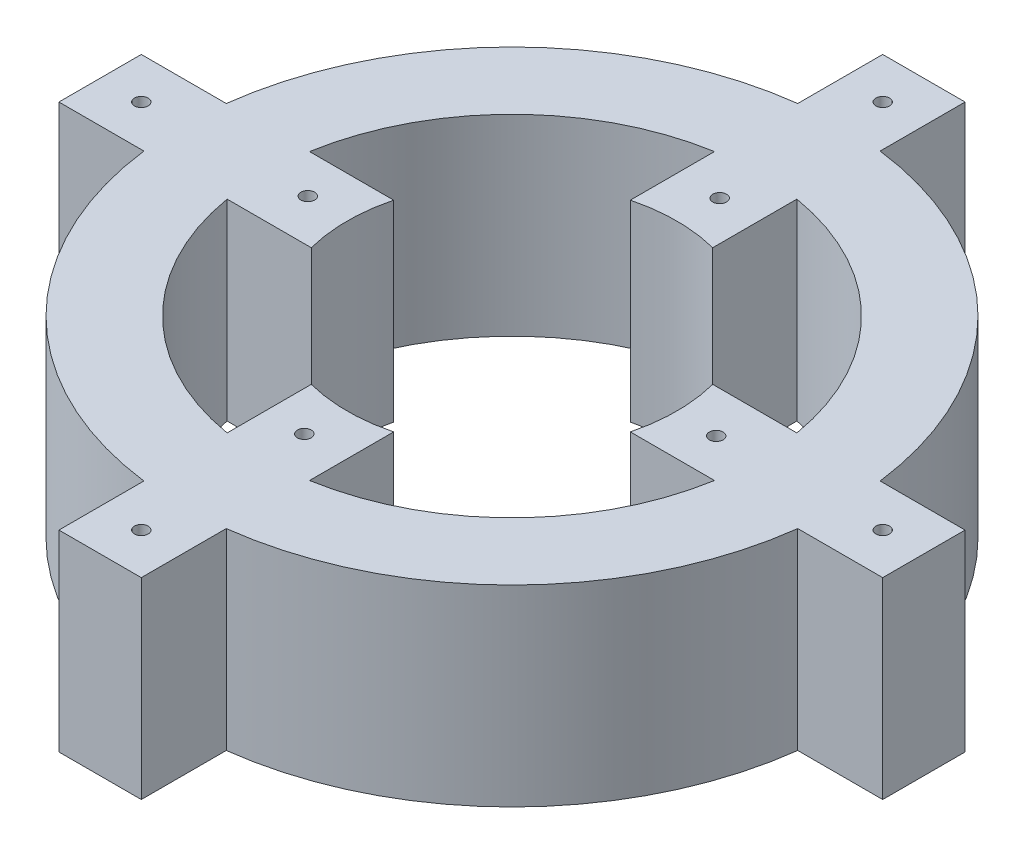
SolidWorks part; units mm, degrees
ref_plane "Спереди" through (0, 0, 0) normal (0, 0, 1) x (1, 0, 0)
ref_plane "Сверху" through (0, 0, 0) normal (0, 1, 0) x (1, 0, 0)
ref_plane "Справа" through (0, 0, 0) normal (1, 0, 0) x (0, 0, -1)
sketch "Эскиз1" plane through (0, 0, 0) normal (0, 1, 0) x (1, 0, 0)
  line L0 (-4.0901, 152.4) -> (-4.0901, -153.2035) construction
  line L1 (-4.0901, -153.2035) -> (-156.4901, -0.8035) construction
  line L2 (-156.4901, -0.8035) -> (148.3099, -0.8035) construction
  line L3 (-111.8532, 106.9595) -> (103.6729, -108.5666) construction
  line L4 (-111.8532, -108.5666) -> (103.6729, 106.9595) construction
  line L5 (-156.4901, 151.5965) -> (-156.4901, -153.2035) construction
  line L6 (-156.4901, -153.2035) -> (148.3099, -153.2035) construction
  line L7 (148.3099, -153.2035) -> (148.3099, 151.5965) construction
  line L8 (148.3099, 151.5965) -> (-156.4901, 151.5965) construction
  line L9 (-118.3901, 113.4965) -> (-118.3901, -115.1035) construction
  line L10 (-118.3901, -115.1035) -> (110.2099, -115.1035) construction
  line L11 (110.2099, -115.1035) -> (110.2099, 113.4965) construction
  line L12 (110.2099, 113.4965) -> (-118.3901, 113.4965) construction
  line L13 (-80.2901, 113.4965) -> (-80.2901, -115.1035) construction
  line L14 (-77.8705, 18.2465) -> (-116.7915, 18.2465)
  line L15 (-194.5901, -0.8035) -> (-80.2901, -0.8035) construction
  line L16 (-77.8705, -19.8535) -> (-116.7915, -19.8535)
  line L17 (-194.5901, 18.2465) -> (-194.5901, -19.8535)
  line L18 (-155.2948, 18.2465) -> (-194.5901, 18.2465)
  line L19 (-155.2948, -19.8535) -> (-194.5901, -19.8535)
  line L20 (14.9599, 189.6965) -> (-23.1401, 189.6965)
  line L21 (14.9599, 150.4012) -> (14.9599, 189.6965)
  line L22 (-23.1401, 150.4012) -> (-23.1401, 189.6965)
  line L23 (14.9599, 72.9768) -> (14.9599, 111.8978)
  line L24 (-23.1401, 72.9768) -> (-23.1401, 111.8978)
  line L27 (-4.0901, 151.5965) -> (-4.0901, -153.2035) construction
  line L28 (-4.0901, 189.6965) -> (-4.0901, 75.3965) construction
  line L29 (186.4099, -19.8535) -> (186.4099, 18.2465)
  line L30 (147.1145, -19.8535) -> (186.4099, -19.8535)
  line L31 (147.1145, 18.2465) -> (186.4099, 18.2465)
  line L32 (69.6902, -19.8535) -> (108.6112, -19.8535)
  line L33 (69.6902, 18.2465) -> (108.6112, 18.2465)
  line L34 (148.3099, -0.8035) -> (-156.4901, -0.8035) construction
  line L35 (186.4099, -0.8035) -> (72.1099, -0.8035) construction
  line L36 (-23.1401, -191.3035) -> (14.9599, -191.3035)
  line L37 (-23.1401, -152.0082) -> (-23.1401, -191.3035)
  line L38 (14.9599, -152.0082) -> (14.9599, -191.3035)
  line L39 (-23.1401, -74.5839) -> (-23.1401, -113.5049)
  line L40 (14.9599, -74.5839) -> (14.9599, -113.5049)
  line L41 (-4.0901, -153.2035) -> (-4.0901, 151.5965) construction
  line L42 (-4.0901, -191.3035) -> (-4.0901, -77.0035) construction
  arc A0 (-155.2948, -19.8535) -> (-111.8532, -108.5666) centre (-4.0901, -0.8035) ccw
  arc A1 (-116.7915, -19.8535) -> (-23.1401, -113.5049) centre (-4.0901, -0.8035) ccw
  arc A2 (-77.8705, 18.2465) -> (-77.8705, -19.8535) centre (-4.0901, -0.8035) ccw
  circle A3 centre (-175.5401, -0.8035) radius 3.175
  circle A4 centre (-99.3401, 0) radius 3.175
  arc A5 (-155.2948, -19.8535) -> (-155.2948, 18.2465) centre (-4.0901, -0.8035) cw construction
  arc A6 (-116.7915, -19.8535) -> (-116.7915, 18.2465) centre (-4.0901, -0.8035) cw construction
  circle A7 centre (-4.0901, 170.6465) radius 3.175
  arc A8 (-23.1401, 150.4012) -> (14.9599, 150.4012) centre (-4.0901, -0.8035) cw construction
  arc A9 (14.9599, 72.9768) -> (-23.1401, 72.9768) centre (-4.0901, -0.8035) ccw
  circle A10 centre (-3.2866, 94.4465) radius 3.175
  arc A11 (-23.1401, 111.8978) -> (14.9599, 111.8978) centre (-4.0901, -0.8035) cw construction
  circle A12 centre (167.3599, -0.8035) radius 3.175
  arc A13 (147.1145, 18.2465) -> (147.1145, -19.8535) centre (-4.0901, -0.8035) cw construction
  arc A14 (69.6902, -19.8535) -> (69.6902, 18.2465) centre (-4.0901, -0.8035) ccw
  circle A15 centre (91.1599, -1.6071) radius 3.175
  arc A16 (108.6112, 18.2465) -> (108.6112, -19.8535) centre (-4.0901, -0.8035) cw construction
  circle A17 centre (-4.0901, -172.2535) radius 3.175
  arc A18 (14.9599, -152.0082) -> (-23.1401, -152.0082) centre (-4.0901, -0.8035) cw construction
  arc A19 (-23.1401, -74.5839) -> (14.9599, -74.5839) centre (-4.0901, -0.8035) ccw
  circle A20 centre (-4.8937, -96.0535) radius 3.175
  arc A21 (14.9599, -113.5049) -> (-23.1401, -113.5049) centre (-4.0901, -0.8035) cw construction
  arc A22 (-23.1401, 150.4012) -> (-111.8532, 106.9595) centre (-4.0901, -0.8035) ccw
  arc A23 (-23.1401, 111.8978) -> (-116.7915, 18.2465) centre (-4.0901, -0.8035) ccw
  arc A24 (108.6112, 18.2465) -> (14.9599, 111.8978) centre (-4.0901, -0.8035) ccw
  arc A25 (147.1145, 18.2465) -> (103.6729, 106.9595) centre (-4.0901, -0.8035) ccw
  arc A26 (14.9599, -113.5049) -> (108.6112, -19.8535) centre (-4.0901, -0.8035) ccw
  arc A27 (14.9599, -152.0082) -> (103.6729, -108.5666) centre (-4.0901, -0.8035) ccw
  arc A29 (-111.8532, 106.9595) -> (-155.2948, 18.2465) centre (-4.0901, -0.8035) ccw
  arc A33 (103.6729, 106.9595) -> (14.9599, 150.4012) centre (-4.0901, -0.8035) ccw
  arc A34 (103.6729, -108.5666) -> (147.1145, -19.8535) centre (-4.0901, -0.8035) ccw
  arc A35 (-111.8532, -108.5666) -> (-23.1401, -152.0082) centre (-4.0901, -0.8035) ccw
  point P5 (0, 0)
  point P21 (60, 0)
  point P43 (38.2522, 11.6949)
  point P99 (-4.0901, -0.8035)
  point P110 (0, 0)
  dimension "D1" = 304.8
  dimension "D5" = 38.1
  dimension "D2" = 228.6
  dimension "D7" = 6.35
  dimension "D14" = 76.2
  dimension "D3" = 45
  dimension "D4" = 90
  dimension "D6" = 19.05
  dimension "D8" = 38.1
  dimension "D9" = 38.1
  dimension "D10" = 38.1
  dimension "D11" = 19.05
  dimension "D12" = 19.05
  dimension "D16" = 381
  dimension "D17" = 381
  dimension "D13" = 4
extrude "Бобышка-Вытянуть1" add sketch "Эскиз1" along normal blind 88.9
